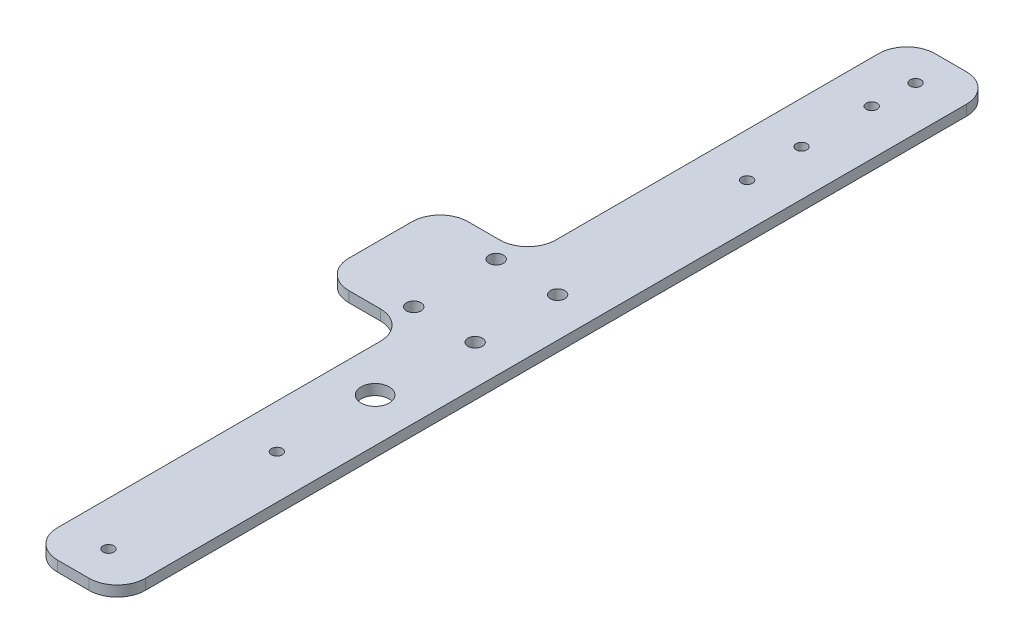
SolidWorks part; units mm, degrees
material "Thornel Mat VMA"
ref_plane "前视基准面" through (0, 0, 0) normal (0, 0, 1) x (1, 0, 0)
ref_plane "上视基准面" through (0, 0, 0) normal (0, 1, 0) x (1, 0, 0)
ref_plane "右视基准面" through (0, 0, 0) normal (1, 0, 0) x (0, 0, -1)
sketch "草图1" plane through (0, 0, 0) normal (0, 1, 0) x (1, 0, 0)
  line L1 (-12.5, 125) -> (12.5, 125)
  line L2 (-12.5, 125) -> (-12.5, -125)
  line L3 (-12.5, -125) -> (12.5, -125)
  line L4 (12.5, 125) -> (12.5, -125)
  line L5 (-12.5, 125) -> (12.5, -125) construction
  line L6 (-12.5, -125) -> (12.5, 125) construction
  line L7 (-37.5, 17) -> (12.5, 17)
  line L8 (-37.5, 17) -> (-37.5, -17)
  line L9 (-37.5, -17) -> (12.5, -17)
  line L10 (12.5, 17) -> (12.5, -17)
  line L11 (-37.5, 17) -> (12.5, -17) construction
  line L12 (-37.5, -17) -> (12.5, 17) construction
  point P0 (0, 0)
  point P6 (-12.5, 0)
  dimension "D1" = 25
  dimension "D2" = 250
  dimension "D3" = 34
extrude "凸台-拉伸1" add sketch "草图1" along normal blind 3 contours L8 L9 L2 L7 | L2 L7 L4 L1 | L2 L9 L4 L7 | L9 L2 L3 L4
ref_plane "基准面1" through (0, 0, 0) normal (0, -1, 0) x (-1, 0, 0)
sketch "草图2" plane through (0, 0, 0) normal (0, -1, 0) x (-1, 0, 0)
  line L0 (-12.5, 0) -> (37.5, 0) construction
  line L1 (-12.5, 125) -> (-12.5, -125) construction
  line L2 (37.5, 17) -> (37.5, -17) construction
  circle A0 centre (-1.25, -11.75) radius 2.05
  circle A1 centre (-1.25, 11.75) radius 2.05
  circle A2 centre (16.25, 11.75) radius 2.05
  circle A3 centre (16.25, -11.75) radius 2.05
  circle A4 centre (0, -115) radius 1.55
  circle A5 centre (0, -67) radius 1.55
  circle A6 centre (0, 115) radius 1.55
  circle A7 centre (0, 67) radius 1.55
extrude "切除-拉伸1" cut sketch "草图2" against normal blind 10
sketch "草图3" plane through (0, 0, 0) normal (0, -1, 0) x (-1, 0, 0)
  line L1 (-12.5, 125) -> (-12.5, -125) construction
  line L2 (12.5, 125) -> (-12.5, 125) construction
  circle A0 centre (0.5, 83) radius 1.55
  circle A1 centre (0.5, 103) radius 1.55
  dimension "D1" = 3.1
  dimension "D2" = 3.1
  dimension "D3" = 20
  dimension "D4" = 22
  dimension "D5" = 13
  dimension "D6" = 13
extrude "切除-拉伸2" cut sketch "草图3" against normal blind 10
fillet "圆角1" radius 8 8 edges at (12.5, 1.5, 125) (-12.5, 1.5, 125) (-12.5, 1.5, 17) (-37.5, 1.5, 17) (-37.5, 1.5, -17) (-12.5, 1.5, -17) (12.5, 1.5, -125) (-12.5, 1.5, -125)
sketch "草图4" plane through (0, 0, 0) normal (0, 1, 0) x (1, 0, 0)
  circle A0 centre (0, -39) radius 4
  circle A1 centre (0, -67) radius 1.55 construction
  dimension "D1" = 28
  dimension "D2" = 8
extrude "切除-拉伸4" cut sketch "草图4" along normal blind 10
